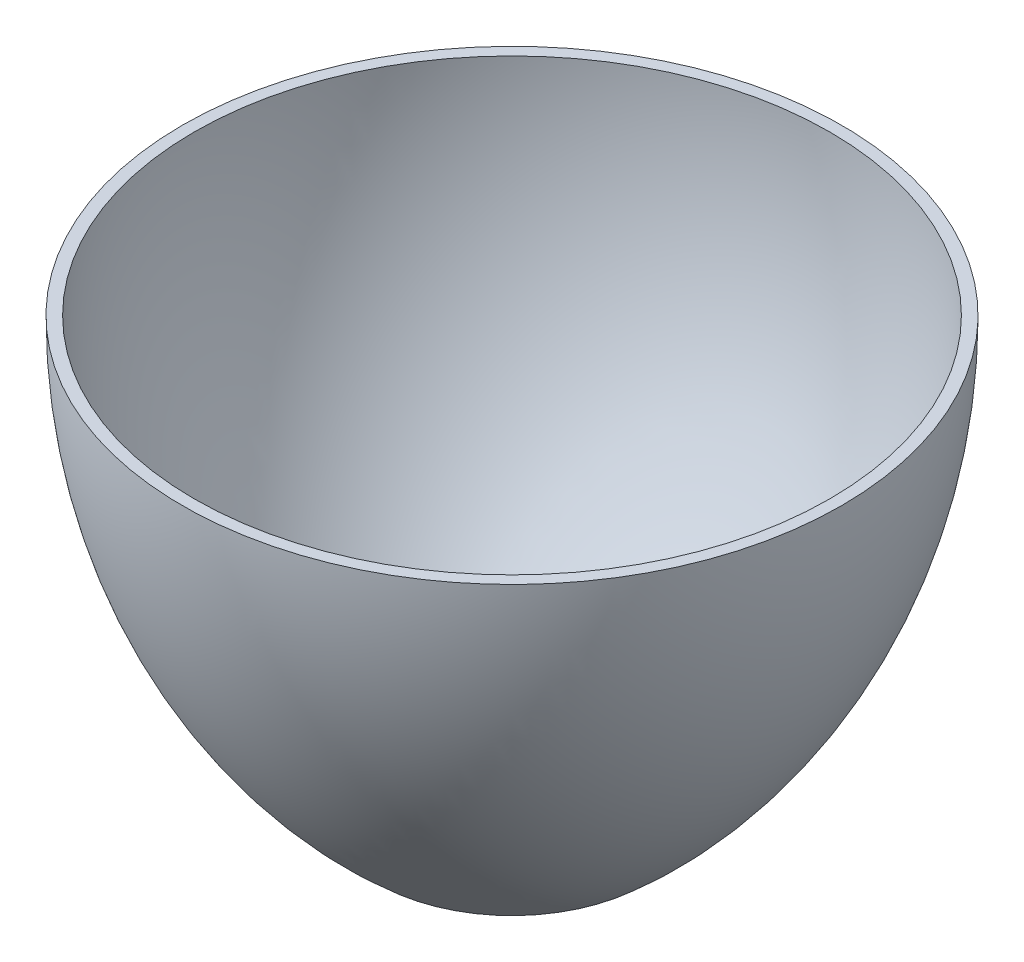
SolidWorks part; units mm, degrees
ref_plane "Front Plane" through (0, 0, 0) normal (0, 0, 1) x (1, 0, 0)
ref_plane "Top Plane" through (0, 0, 0) normal (0, 1, 0) x (1, 0, 0)
ref_plane "Right Plane" through (0, 0, 0) normal (1, 0, 0) x (0, 0, -1)
sketch "Sketch1" plane through (0, 0, 0) normal (0, 0, 1) x (1, 0, 0)
  line L0 (0, 0) -> (0, -114.3)
  line L1 (0, 0) -> (85.725, 0)
  line L3 (0, -114.3) -> (0, -279.4)
  line L4 (0, -279.4) -> (31.75, -279.4)
  line L5 (31.75, -279.4) -> (31.75, -266.7)
  line L6 (31.75, -266.7) -> (133.35, -266.7)
  line L7 (31.75, -114.3) -> (31.75, -241.3)
  line L9 (31.75, -241.3) -> (133.35, -241.3)
  line L10 (133.35, -241.3) -> (133.35, -266.7)
  line L11 (0, -114.3) -> (31.75, -114.3)
  arc A2 (85.725, 0) -> (31.75, -114.3) centre (-62.286, 0) cw
  dimension "D1" = 85.725
  dimension "D2" = 114.3
  dimension "D3" = 31.75
  dimension "D4" = 165.1
  dimension "D5" = 12.7
  dimension "D6" = 101.6
  dimension "D7" = 25.4
revolve "Revolve1" add sketch "Sketch1" angle 360 about L0
shell "Shell1" thickness 3.175
